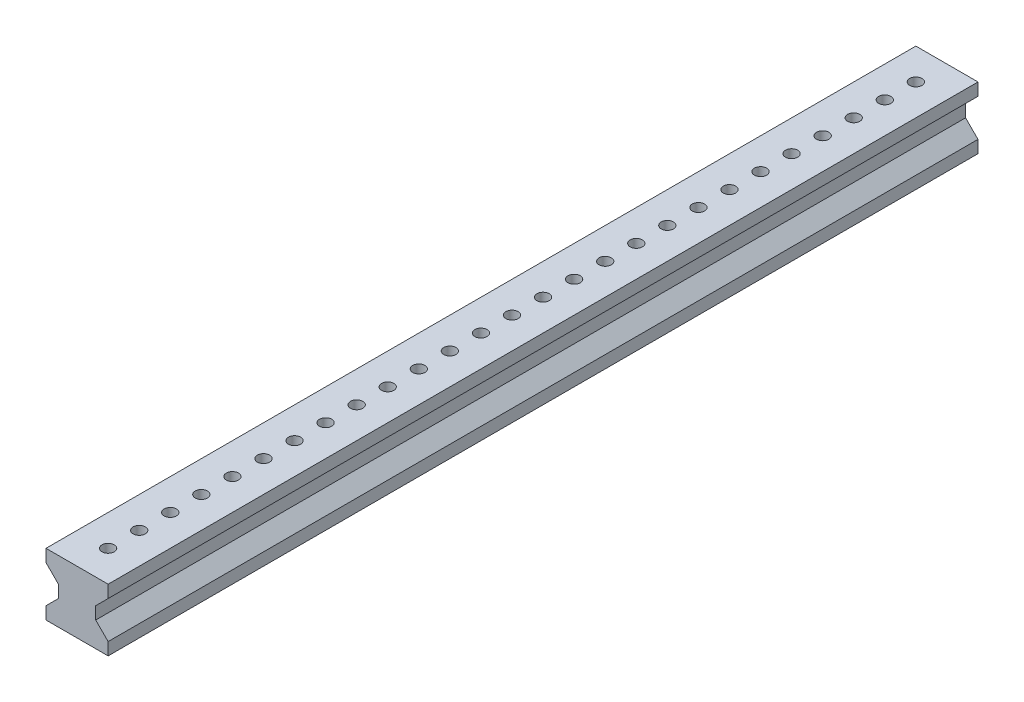
SolidWorks part; units mm, degrees
ref_plane "Front Plane" through (0, 0, 0) normal (0, 0, 1) x (1, 0, 0)
ref_plane "Top Plane" through (0, 0, 0) normal (0, 1, 0) x (1, 0, 0)
ref_plane "Right Plane" through (0, 0, 0) normal (1, 0, 0) x (0, 0, -1)
sketch "Sketch1" plane through (0, 0, 0) normal (0, 0, 1) x (1, 0, 0)
  line L0 (12.7, 12.7) -> (-12.7, 12.7)
  line L1 (-12.7, 12.7) -> (-12.7, 7.62)
  line L2 (-12.7, 7.62) -> (-7.62, 2.54)
  line L3 (-7.62, 2.54) -> (-7.62, -2.54)
  line L4 (-7.62, -2.54) -> (-12.7, -7.62)
  line L5 (-12.7, -7.62) -> (-12.7, -12.7)
  line L6 (-12.7, -12.7) -> (12.7, -12.7)
  line L7 (0, 0) -> (0, 22.2161) construction
  line L8 (12.7, -7.62) -> (12.7, -12.7)
  line L9 (7.62, -2.54) -> (12.7, -7.62)
  line L10 (7.62, 2.54) -> (7.62, -2.54)
  line L11 (12.7, 7.62) -> (7.62, 2.54)
  line L12 (12.7, 12.7) -> (12.7, 7.62)
  point P8 (-7.62, 0)
  point P13 (0, -12.7)
  point P18 (0, 12.7)
  dimension "D1" = 5.08
  dimension "D2" = 5.08
  dimension "D3" = 5.08
  dimension "D4" = 25.4
  dimension "D5" = 12.7
  dimension "D6" = 5.08
extrude "Boss-Extrude1" add sketch "Sketch1" along normal blind 355.6
sketch "Sketch3" plane through (0, 12.7, 0) normal (0, 1, 0) x (1, 0, 0)
  line L0 (12.7, -355.6) -> (-12.7, -355.6) construction
  line L1 (0, -355.6) -> (0, -10.2) construction
  circle A0 centre (0, -342.9) radius 2.5
  circle A1 centre (0, -330.2) radius 2.5
  circle A2 centre (0, -317.5) radius 2.5
  circle A3 centre (0, -304.8) radius 2.5
  circle A4 centre (0, -292.1) radius 2.5
  circle A5 centre (0, -279.4) radius 2.5
  circle A6 centre (0, -266.7) radius 2.5
  circle A7 centre (0, -254) radius 2.5
  circle A8 centre (0, -241.3) radius 2.5
  circle A9 centre (0, -228.6) radius 2.5
  circle A10 centre (0, -215.9) radius 2.5
  circle A11 centre (0, -203.2) radius 2.5
  circle A12 centre (0, -190.5) radius 2.5
  circle A13 centre (0, -177.8) radius 2.5
  circle A14 centre (0, -165.1) radius 2.5
  circle A15 centre (0, -152.4) radius 2.5
  circle A16 centre (0, -139.7) radius 2.5
  circle A17 centre (0, -127) radius 2.5
  circle A18 centre (0, -114.3) radius 2.5
  circle A19 centre (0, -101.6) radius 2.5
  circle A20 centre (0, -88.9) radius 2.5
  circle A21 centre (0, -76.2) radius 2.5
  circle A22 centre (0, -63.5) radius 2.5
  circle A23 centre (0, -50.8) radius 2.5
  circle A24 centre (0, -38.1) radius 2.5
  circle A25 centre (0, -25.4) radius 2.5
  circle A26 centre (0, -12.7) radius 2.5
  arc A28 (0, -2.5) -> (0, 2.5) centre (0, 0) ccw [skipped]
  point P5 (0, -355.6)
  dimension "D1" = 5
  dimension "D2" = 12.7
  dimension "D3" = 28
extrude "Cut-Extrude1" cut sketch "Sketch3" against normal up to surface (25.4 mm away) up to face at (0, -12.7, 177.8)
